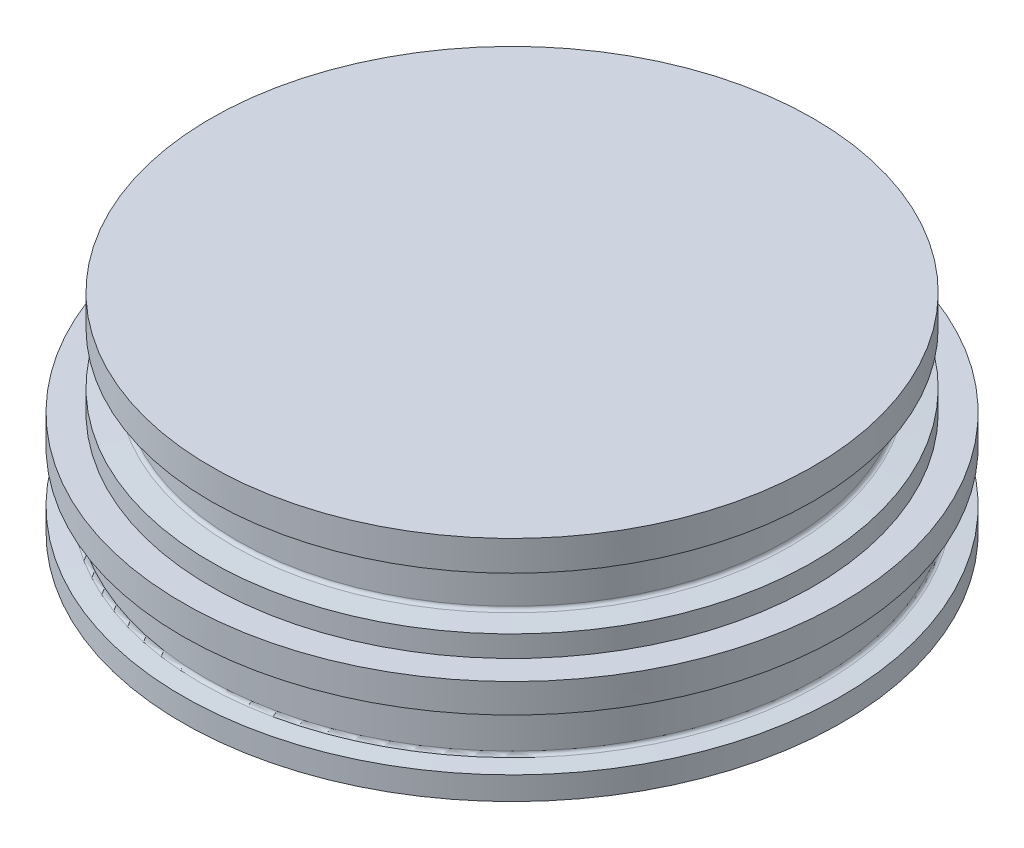
SolidWorks part; units mm, degrees
material "6061 Alloy"
ref_plane "Front Plane" through (0, 0, 0) normal (0, 0, 1) x (1, 0, 0)
ref_plane "Top Plane" through (0, 0, 0) normal (0, 1, 0) x (1, 0, 0)
ref_plane "Right Plane" through (0, 0, 0) normal (1, 0, 0) x (0, 0, -1)
sketch "Sketch1" plane through (0, 0, 0) normal (0, 0, 1) x (1, 0, 0)
  line L0 (0, 0) -> (0, 15.8533) construction
  line L1 (-22.0853, 0) -> (-22.0853, -7.62)
  line L2 (-22.0853, -7.62) -> (-24.1554, -7.62)
  line L3 (-24.1554, -7.62) -> (-24.1554, -15.24)
  line L4 (-22.0853, 0) -> (0, 0)
  line L5 (-24.1554, -15.24) -> (0, -15.24)
  line L6 (0, -15.24) -> (0, 0)
  dimension "D1" = 48.3108
  dimension "D2" = 44.1706
  dimension "D3" = 7.62
  dimension "D4" = 15.24
revolve "Revolve1" add sketch "Sketch1" angle 360 about L0
ref_plane "Plane1" through (0, 0, 0) normal (-1, 0, 0) x (0, 0, -1)
ref_plane "Plane2" through (0, 0, 0) normal (-1, 0, 0) x (0, 0, -1)
ref_plane "Plane3" through (0, 0, 0) normal (-1, 0, 0) x (0, 0, -1)
sketch "Sketch7" plane through (0, 0, 0) normal (-1, 0, 0) x (0, 0, -1)
  line L0 (22.7744, 13.425) -> (24.6888, 13.5925)
  line L1 (24.6888, 13.5925) -> (24.6888, 9.7015)
  line L2 (24.6888, 9.7015) -> (22.7744, 9.869)
  line L3 (22.5425, 10.1221) -> (22.5425, 13.172)
  line L4 (0, 50) -> (0, -50) construction
  arc A0 (22.7744, 9.869) -> (22.5425, 10.1221) centre (22.7965, 10.1221) cw
  arc A1 (22.5425, 13.172) -> (22.7744, 13.425) centre (22.7965, 13.172) cw
revolve "Groove for AS 568-132, O-Ring1" cut sketch "Sketch7"
ref_plane "Plane4" through (0, 0, 0) normal (-1, 0, 0) x (0, 0, -1)
sketch "Sketch9" plane through (0, 0, 0) normal (-1, 0, 0) x (0, 0, -1)
  line L0 (20.3995, 5.914) -> (22.3139, 6.0815)
  line L1 (22.3139, 6.0815) -> (22.3139, 2.1905)
  line L2 (22.3139, 2.1905) -> (20.3995, 2.358)
  line L3 (20.1676, 2.611) -> (20.1676, 5.661)
  line L4 (0, 50) -> (0, -50) construction
  arc A0 (20.3995, 2.358) -> (20.1676, 2.611) centre (20.4216, 2.611) cw
  arc A1 (20.1676, 5.661) -> (20.3995, 5.914) centre (20.4216, 5.661) cw
revolve "Groove for AS 568-129, O-Ring1" cut sketch "Sketch9" angle 360 about L4
